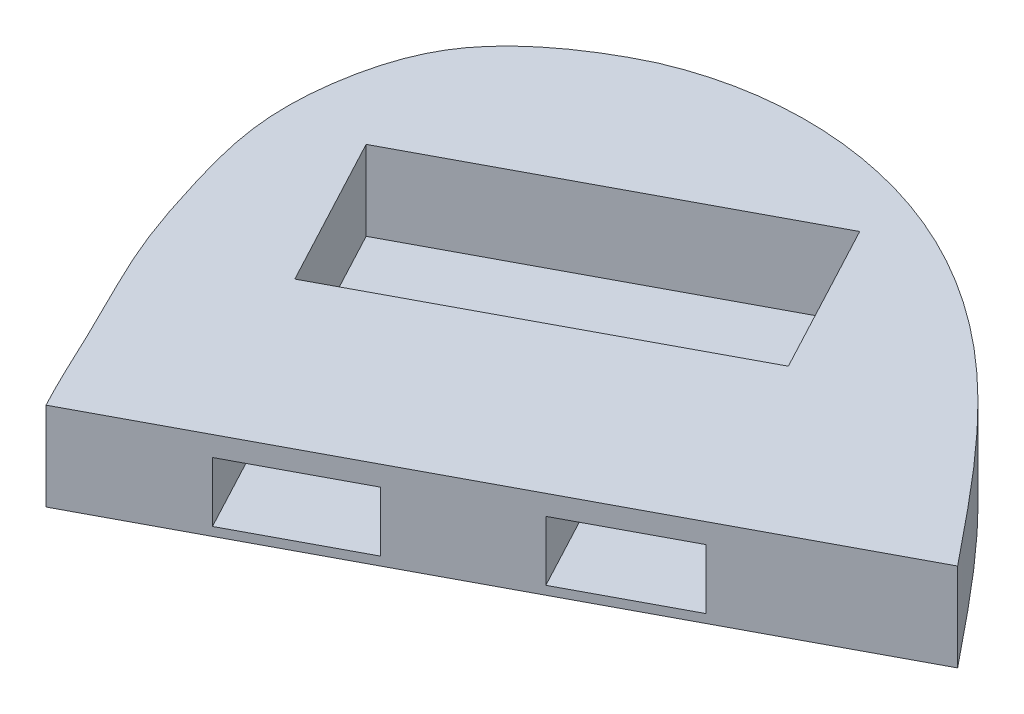
SolidWorks part; units mm, degrees
ref_plane "Front Plane" through (0, 0, 0) normal (0, 0, 1) x (1, 0, 0)
ref_plane "Top Plane" through (0, 0, 0) normal (0, 1, 0) x (1, 0, 0)
ref_plane "Right Plane" through (0, 0, 0) normal (1, 0, 0) x (0, 0, -1)
sketch "Sketch2" plane through (0, 0, 0) normal (0, 1, 0) x (1, 0, 0)
  line L0 (0, 127) -> (0, -127) construction
  line L1 (0, 127) -> (0, 130.71) construction
  line L2 (0, -127) -> (0, -136.1) construction
  line L3 (0, 130.71) -> (41.775, 130.71) construction
  line L4 (0, 127) -> (23.05, 127) construction
  line L5 (23.05, 127) -> (61.7, 127) construction
  line L6 (0, 114.3) -> (6.41, 114.3) construction
  line L7 (6.41, 114.3) -> (83.23, 114.3) construction
  line L8 (0, 101.6) -> (1.49, 101.6) construction
  line L9 (1.49, 101.6) -> (96.56, 101.6) construction
  line L10 (0, 88.9) -> (0.99, 88.9) construction
  line L11 (0.99, 88.9) -> (107.25, 88.9) construction
  line L12 (0, 76.2) -> (3.89, 76.2) construction
  line L13 (3.89, 76.2) -> (117.43, 76.2) construction
  line L14 (0, 63.5) -> (8.377, 63.5) construction
  line L15 (8.377, 63.5) -> (126.33, 63.5) construction
  line L16 (0, 50.8) -> (14.48, 50.8) construction
  line L17 (14.48, 50.8) -> (131.99, 50.8) construction
  line L18 (0, 38.1) -> (20.61, 38.1) construction
  line L19 (20.61, 38.1) -> (137.22, 38.1) construction
  line L20 (0, 25.4) -> (28.08, 25.4) construction
  line L21 (28.08, 25.4) -> (142.02, 25.4) construction
  line L22 (0, 12.7) -> (37.94, 12.7) construction
  line L23 (37.94, 12.7) -> (147.27, 12.7) construction
  line L24 (0, 0) -> (49.95, 0) construction
  line L25 (49.95, 0) -> (151.58, 0) construction
  line L26 (0, -12.7) -> (63.58, -12.7) construction
  line L27 (63.58, -12.7) -> (156.31, -12.7) construction
  line L28 (0, -25.4) -> (77.09, -25.4) construction
  line L29 (77.09, -25.4) -> (161.56, -25.4) construction
  line L30 (0, -38.1) -> (87.91, -38.1) construction
  line L31 (87.91, -38.1) -> (166.92, -38.1) construction
  line L32 (0, -50.8) -> (96.68, -50.8) construction
  line L33 (96.68, -50.8) -> (173.06, -50.8) construction
  line L34 (0, -63.5) -> (102.39, -63.5) construction
  line L35 (102.39, -63.5) -> (179.38, -63.5) construction
  line L36 (0, -76.2) -> (107.05, -76.2) construction
  line L37 (107.05, -76.2) -> (184.61, -76.2) construction
  line L38 (0, -88.9) -> (112.04, -88.9) construction
  line L39 (112.04, -88.9) -> (187.8, -88.9) construction
  line L40 (0, -101.6) -> (116.71, -101.6) construction
  line L41 (116.71, -101.6) -> (188.88, -101.6) construction
  line L42 (0, -114.3) -> (122.9, -114.3) construction
  line L43 (122.9, -114.3) -> (186.67, -114.3) construction
  line L44 (0, -127) -> (134.38, -127) construction
  line L45 (134.38, -127) -> (177.82, -127) construction
  line L46 (0, -136.1) -> (161.96, -136.1) construction
  spline S0 degree 3 poles (23.05, 127) (22.9432, 126.9029) (6.6209, 120.0211) (0.9311, 101.489) (0.324, 88.7192) (3.8259, 76.0059) (8.1075, 63.1658) (14.6225, 50.8573) (20.4776, 37.8047) (28.0274, 24.8193) (38.0542, 12.1741) (50.087, -0.4139) (63.5159, -12.7149) (76.995, -24.6371) (87.7537, -37.6768) (96.9513, -50.0664) (102.4906, -63.3377) (106.9152, -76.2857) (112.1884, -88.8151) (116.5558, -101.8299) (122.7605, -115.6564) (136.3433, -130.1881) (151.9988, -139.0292) (161.96, -136.1) knots 0 0 0 0 0.090945 0.126642 0.163655 0.201592 0.240817 0.28185 0.322918 0.365826 0.412648 0.463551 0.517804 0.571802 0.620389 0.665335 0.705886 0.745282 0.785019 0.824424 0.865568 0.915423 1 1 1 1
  spline S1 degree 3 poles (161.96, -136.1) (172.4316, -132.9237) (186.6003, -121.7153) (189.3991, -101.6091) (188.0813, -88.7382) (184.8895, -75.8761) (179.4567, -63.2893) (173.0415, -50.8419) (166.7998, -38.2708) (161.6037, -25.3961) (156.2483, -12.7941) (151.4502, -0.0964) (147.5268, 12.9147) (141.8259, 25.264) (137.3702, 38.2209) (131.8751, 50.795) (126.7062, 64.3168) (117.2823, 76.4516) (103.4204, 93.7595) (86.8424, 113.3106) (58.2005, 131.1531) (35.3863, 132.2876) (23.05, 127) knots 0 0 0 0 0.095094 0.131399 0.167296 0.204175 0.242857 0.282809 0.322537 0.36136 0.400064 0.438232 0.476003 0.514706 0.552944 0.591626 0.630785 0.674461 0.720302 0.818758 0.889158 1 1 1 1
  point P2 (0, 0)
  point P3 (0, 114.3)
  point P8 (0, 101.6)
  point P9 (0, 88.9)
  point P10 (0, 76.2)
  point P11 (0, 63.5)
  point P12 (0, 50.8)
  point P13 (0, 38.1)
  point P14 (0, 25.4)
  point P15 (0, 12.7)
  point P16 (0, 0)
  point P17 (0, -12.7)
  point P18 (0, -25.4)
  point P19 (0, -38.1)
  point P20 (0, -50.8)
  point P21 (0, -63.5)
  point P22 (0, -76.2)
  point P23 (0, -88.9)
  point P24 (0, -101.6)
  point P25 (0, -114.3)
  dimension "D1" = 254
  dimension "D2" = 9.1
  dimension "D3" = 3.71
  dimension "D4" = 12.7
  dimension "D6" = 12.7
  dimension "D7" = 41.775
  dimension "D8" = 23.05
  dimension "D9" = 6.41
  dimension "D10" = 1.49
  dimension "D11" = 0.99
  dimension "D12" = 3.89
  dimension "D13" = 8.377
  dimension "D14" = 14.48
  dimension "D15" = 20.61
  dimension "D16" = 28.08
  dimension "D17" = 37.94
  dimension "D18" = 49.95
  dimension "D19" = 63.58
  dimension "D20" = 77.09
  dimension "D21" = 87.91
  dimension "D22" = 96.68
  dimension "D23" = 102.39
  dimension "D24" = 107.05
  dimension "D25" = 112.04
  dimension "D26" = 116.71
  dimension "D27" = 122.9
  dimension "D28" = 134.38
  dimension "D29" = 161.96
  dimension "D30" = 177.82
  dimension "D31" = 186.67
  dimension "D32" = 188.88
  dimension "D33" = 187.8
  dimension "D34" = 184.61
  dimension "D35" = 179.38
  dimension "D36" = 173.06
  dimension "D37" = 166.92
  dimension "D38" = 161.56
  dimension "D39" = 156.31
  dimension "D40" = 151.58
  dimension "D41" = 147.27
  dimension "D42" = 142.02
  dimension "D43" = 137.22
  dimension "D44" = 131.99
  dimension "D45" = 126.33
  dimension "D46" = 117.43
  dimension "D47" = 107.25
  dimension "D48" = 96.56
  dimension "D49" = 83.23
  dimension "D50" = 61.7
  dimension "D5" = 19
extrude "Boss-Extrude1" add sketch "Sketch2" against normal blind 1.3
sketch "Sketch3" plane through (0, 0, 0) normal (0, 1, 0) x (1, 0, 0)
  line L8 (0, 0) -> (21.6201, 11.4956)
  line L9 (0, 0) -> (0, 15.1041)
  line L10 (21.582, 36.2367) -> (111.2769, 83.9284)
  line L11 (48.1587, 84.3449) -> (62.2429, 57.8565) construction
  line L14 (11.6714, 94.3911) -> (23.8777, 71.4345)
  line L15 (23.8777, 71.4345) -> (72.4398, 97.2554)
  line L16 (72.4398, 97.2554) -> (60.2335, 120.212)
  line L17 (60.2335, 120.212) -> (11.6714, 94.3911)
  spline S3 degree 3 poles (2494.4744, 1728.3066) (-340.0594, -118.5188) (174.5854, -208.0295) (189.3991, -101.6091) (188.0813, -88.7382) (184.8895, -75.8761) (179.4567, -63.2893) (173.0415, -50.8419) (166.7998, -38.2708) (161.6037, -25.3961) (156.2483, -12.7941) (151.4502, -0.0964) (147.5268, 12.9147) (141.8259, 25.264) (137.3702, 38.2209) (131.8751, 50.795) (126.7062, 64.3168) (117.2823, 76.4516) (103.4204, 93.7595) (86.8424, 113.3106) (-33.8537, 188.4984) (-295.593, -112.977) (1752.8503, -2292.2407) knots -0.718189 -0.718189 -0.718189 -0.718189 0.095094 0.131399 0.167296 0.204175 0.242857 0.282809 0.322537 0.36136 0.400064 0.438232 0.476003 0.514706 0.552944 0.591626 0.630785 0.674461 0.720302 0.818758 0.889158 1.898943 1.898943 1.898943 1.898943 only from (161.96, -136.1) to (23.05, 127)
  spline S4 degree 3 poles (-2938.7907, -342.8869) (287.3165, 82.3384) (22.1863, 170.7191) (0.9311, 101.489) (0.324, 88.7192) (3.8259, 76.0059) (8.1075, 63.1658) (14.6225, 50.8573) (20.4776, 37.8047) (28.0274, 24.8193) (38.0542, 12.1741) (50.087, -0.4139) (63.5159, -12.7149) (76.995, -24.6371) (87.7537, -37.6768) (96.9513, -50.0664) (102.4906, -63.3377) (106.9152, -76.2857) (112.1884, -88.8151) (116.5558, -101.8299) (122.7605, -115.6564) (177.6466, -174.3769) (359.2507, -173.2107) (-131.2675, 2843.0815) knots -0.447709 -0.447709 -0.447709 -0.447709 0.090945 0.126642 0.163655 0.201592 0.240817 0.28185 0.322918 0.365826 0.412648 0.463551 0.517804 0.571802 0.620389 0.665335 0.705886 0.745282 0.785019 0.824424 0.865568 0.915423 1.533901 1.533901 1.533901 1.533901 only from (23.05, 127) to (161.96, -136.1)
  spline S5 degree 3 poles (161.96, -136.1) (172.4316, -132.9237) (186.6003, -121.7153) (189.3991, -101.6091) (188.0813, -88.7382) (184.8895, -75.8761) (179.4567, -63.2893) (173.0415, -50.8419) (166.7998, -38.2708) (161.6037, -25.3961) (156.2483, -12.7941) (151.4502, -0.0964) (147.5268, 12.9147) (141.8259, 25.264) (137.3702, 38.2209) (131.8751, 50.795) (126.7062, 64.3168) (117.2823, 76.4516) (103.4204, 93.7595) (86.8424, 113.3106) (58.2005, 131.1531) (35.3863, 132.2876) (23.05, 127) knots 0 0 0 0 0.095094 0.131399 0.167296 0.204175 0.242857 0.282809 0.322537 0.36136 0.400064 0.438232 0.476003 0.514706 0.552944 0.591626 0.630785 0.674461 0.720302 0.818758 0.889158 1 1 1 1
  spline S6 degree 3 poles (23.05, 127) (22.9432, 126.9029) (6.6209, 120.0211) (0.9311, 101.489) (0.324, 88.7192) (3.8259, 76.0059) (8.1075, 63.1658) (14.6225, 50.8573) (20.4776, 37.8047) (28.0274, 24.8193) (38.0542, 12.1741) (50.087, -0.4139) (63.5159, -12.7149) (76.995, -24.6371) (87.7537, -37.6768) (96.9513, -50.0664) (102.4906, -63.3377) (106.9152, -76.2857) (112.1884, -88.8151) (116.5558, -101.8299) (122.7605, -115.6564) (136.3433, -130.1881) (151.9988, -139.0292) (161.96, -136.1) knots 0 0 0 0 0.090945 0.126642 0.163655 0.201592 0.240817 0.28185 0.322918 0.365826 0.412648 0.463551 0.517804 0.571802 0.620389 0.665335 0.705886 0.745282 0.785019 0.824424 0.865568 0.915423 1 1 1 1
  dimension "D1" = 118
  dimension "D2" = 55
  dimension "D3" = 26
  dimension "D4" = 30
  dimension "D6" = 0
extrude "Boss-Extrude2" add sketch "Sketch3" along normal blind 12
sketch "Sketch6" plane through (0, 0, 0) normal (0, 1, 0) x (1, 0, 0)
  line L1 (111.2769, 83.9284) -> (21.582, 36.2367)
  line L2 (111.2769, 83.9284) -> (21.582, 36.2367)
  spline S2 degree 3 poles (-1143.2328, -2727.0292) (203.5773, 586.4825) (-81.704, 163.2052) (38.0542, 12.1741) (50.087, -0.4139) (63.5159, -12.7149) (76.995, -24.6371) (87.7537, -37.6768) (96.9513, -50.0664) (102.4906, -63.3377) (106.9152, -76.2857) (112.1884, -88.8151) (116.5558, -101.8299) (122.7605, -115.6564) (177.6476, -174.378) (359.2577, -173.2107) (-131.2984, 2843.2712) knots -1.216144 -1.216144 -1.216144 -1.216144 0.365826 0.412648 0.463551 0.517804 0.571802 0.620389 0.665335 0.705886 0.745282 0.785019 0.824424 0.865568 0.915423 1.533914 1.533914 1.533914 1.533914 only from (21.582, 36.2367) to (161.96, -136.1)
  spline S3 degree 3 poles (2494.5229, 1728.3382) (-340.065, -118.5178) (174.5853, -208.03) (189.3991, -101.6091) (188.0813, -88.7382) (184.8895, -75.8761) (179.4567, -63.2893) (173.0415, -50.8419) (166.7998, -38.2708) (161.6037, -25.3961) (156.2483, -12.7941) (151.4502, -0.0964) (147.5268, 12.9147) (141.8259, 25.264) (137.3702, 38.2209) (131.8751, 50.795) (126.7062, 64.3168) (-0.4877, 228.0996) (-141.1102, 316.4332) (-2110.3873, 2099.6983) knots -0.718193 -0.718193 -0.718193 -0.718193 0.095094 0.131399 0.167296 0.204175 0.242857 0.282809 0.322537 0.36136 0.400064 0.438232 0.476003 0.514706 0.552944 0.591626 0.630785 0.674461 2.328358 2.328358 2.328358 2.328358 only from (161.96, -136.1) to (111.2769, 83.9284)
  spline S4 degree 3 poles (21.582, 36.2367) (23.56, 32.5167) (28.4636, 24.2691) (38.0542, 12.1741) (50.087, -0.4139) (63.5159, -12.7149) (76.995, -24.6371) (87.7537, -37.6768) (96.9513, -50.0664) (102.4906, -63.3377) (106.9152, -76.2857) (112.1884, -88.8151) (116.5558, -101.8299) (122.7605, -115.6564) (136.3433, -130.1881) (151.9988, -139.0292) (161.96, -136.1) knots 0.329036 0.329036 0.329036 0.329036 0.365826 0.412648 0.463551 0.517804 0.571802 0.620389 0.665335 0.705886 0.745282 0.785019 0.824424 0.865568 0.915423 1 1 1 1
  spline S5 degree 3 poles (161.96, -136.1) (172.4316, -132.9237) (186.6003, -121.7153) (189.3991, -101.6091) (188.0813, -88.7382) (184.8895, -75.8761) (179.4567, -63.2893) (173.0415, -50.8419) (166.7998, -38.2708) (161.6037, -25.3961) (156.2483, -12.7941) (151.4502, -0.0964) (147.5268, 12.9147) (141.8259, 25.264) (137.3702, 38.2209) (131.8751, 50.795) (126.7062, 64.3168) (118.6026, 74.7514) (113.3381, 81.3659) (111.2769, 83.9284) knots 0 0 0 0 0.095094 0.131399 0.167296 0.204175 0.242857 0.282809 0.322537 0.36136 0.400064 0.438232 0.476003 0.514706 0.552944 0.591626 0.630785 0.674461 0.702273 0.702273 0.702273 0.702273
  dimension "D1" = 0
extrude "Cut to remove bot sole" cut sketch "Sketch6" against normal through all both contours L2 S4 S5
sketch "Sketch7" plane through (-10.2641, 0, -19.3039) normal (0.4695, 0, 0.8829) x (0.8829, 0, -0.4695)
  line L0 (82.5474, 6) -> (82.5474, 0) construction
  line L1 (82.5474, 12) -> (82.5474, 6) construction
  line L2 (82.5474, 6) -> (109.6192, 6) construction
  line L3 (82.5474, 6) -> (54.6192, 6) construction
  line L4 (54.6192, 0) -> (109.6192, 0)
  line L5 (54.6192, 12) -> (54.6192, 0)
  line L6 (109.6192, 12) -> (54.6192, 12)
  line L7 (109.6192, 0) -> (109.6192, 12)
  line L8 (54.6192, 0) -> (109.6192, 0)
  line L9 (54.6192, 12) -> (54.6192, 0)
  line L10 (109.6192, 12) -> (54.6192, 12)
  line L11 (109.6192, 0) -> (109.6192, 12)
  line L12 (73.3267, 9) -> (91.7681, 9)
  line L13 (73.3267, 9) -> (54.6192, 9)
  line L14 (54.6192, 9) -> (73.3267, 9)
  line L15 (73.3267, 9) -> (73.3267, 0)
  line L16 (91.7681, 9) -> (91.7681, 0)
  line L17 (91.7681, 9) -> (109.6192, 9)
  point P12 (82.5474, 9)
  dimension "D1" = 0
extrude "Cut-Extrude4" cut sketch "Sketch7" against normal up to next contours L15 L13 L9 L8 | L17 L16 L8 L11
